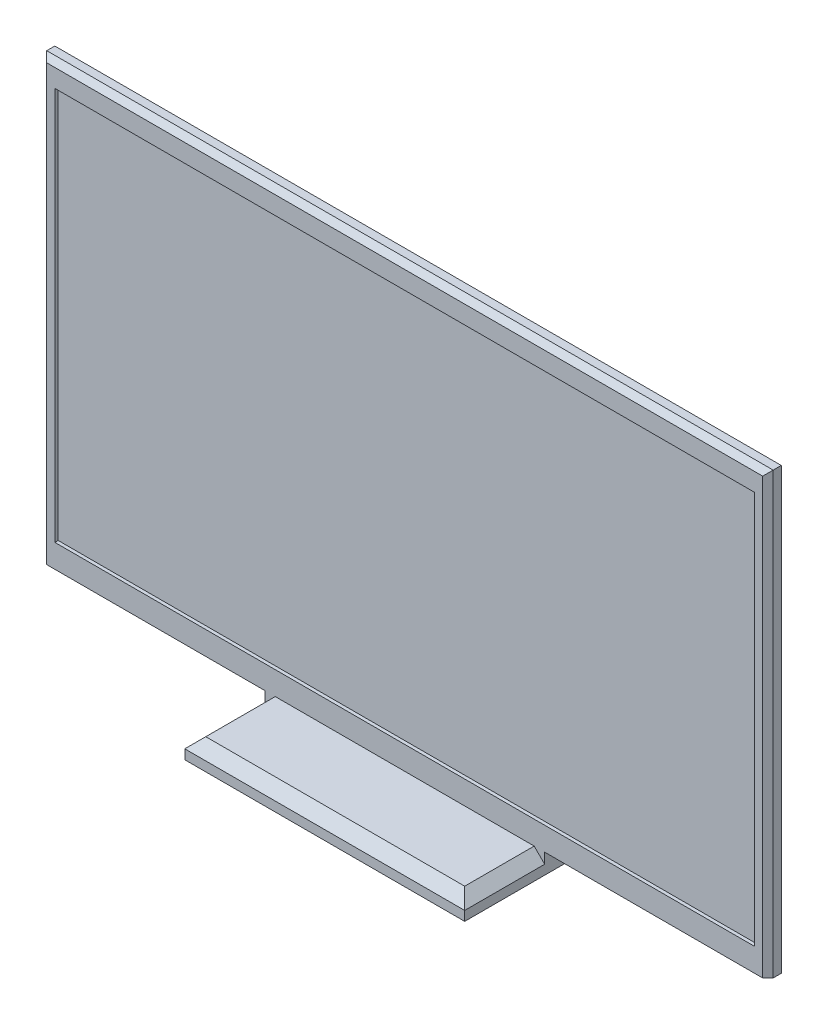
SolidWorks part; units mm, degrees
ref_plane "Front Plane" through (0, 0, 0) normal (0, 0, 1) x (1, 0, 0)
ref_plane "Top Plane" through (0, 0, 0) normal (0, 1, 0) x (1, 0, 0)
ref_plane "Right Plane" through (0, 0, 0) normal (1, 0, 0) x (0, 0, -1)
sketch "Sketch1" plane through (0, 0, 0) normal (0, 0, 1) x (1, 0, 0)
  line L1 (-692.15, -419.1) -> (692.15, -419.1)
  line L2 (-692.15, -419.1) -> (-692.15, 419.1)
  line L3 (-692.15, 419.1) -> (692.15, 419.1)
  line L4 (692.15, -419.1) -> (692.15, 419.1)
  line L5 (-692.15, -419.1) -> (692.15, 419.1) construction
  line L6 (-692.15, 419.1) -> (692.15, -419.1) construction
  point P0 (0, 0)
  dimension "D1" = 838.2
  dimension "D2" = 1384.3
extrude "Boss-Extrude1" add sketch "Sketch1" along normal blind 25.4
chamfer "Chamfer1" distance 10 angle 45 3 edges at (-692.15, 0, 25.4) (692.15, 0, 25.4) (0, 419.1, 25.4)
sketch "Sketch2" plane through (0, 0, 25.4) normal (0, 0, 1) x (1, 0, 0)
  line L1 (-666.75, -374.65) -> (666.75, -374.65)
  line L2 (-666.75, -374.65) -> (-666.75, 374.65)
  line L3 (-666.75, 374.65) -> (666.75, 374.65)
  line L4 (666.75, -374.65) -> (666.75, 374.65)
  line L5 (-666.75, -374.65) -> (666.75, 374.65) construction
  line L6 (-666.75, 374.65) -> (666.75, -374.65) construction
  point P0 (0, 0)
  dimension "D1" = 749.3
  dimension "D2" = 1333.5
extrude "Cut-Extrude1" cut sketch "Sketch2" against normal blind 6.35
sketch "Sketch3" plane through (0, -419.1, 0) normal (0, -1, 0) x (1, 0, 0)
  line L0 (-682.15, 25.4) -> (682.15, 25.4) construction
  line L1 (-266.7, -152.4) -> (266.7, -152.4)
  line L2 (-266.7, -152.4) -> (-266.7, 177.8)
  line L3 (-266.7, 177.8) -> (266.7, 177.8)
  line L4 (266.7, -152.4) -> (266.7, 177.8)
  line L5 (0, 177.8) -> (0, 0) construction
  dimension "D1" = 330.2
  dimension "D2" = 533.4
  dimension "D3" = 152.4
extrude "Boss-Extrude2" add sketch "Sketch3" along normal blind 38.1
chamfer "Chamfer2" distance 20 angle 45 3 edges at (266.7, -419.1, 101.6) (-266.7, -419.1, 101.6) (0, -419.1, 177.8)
